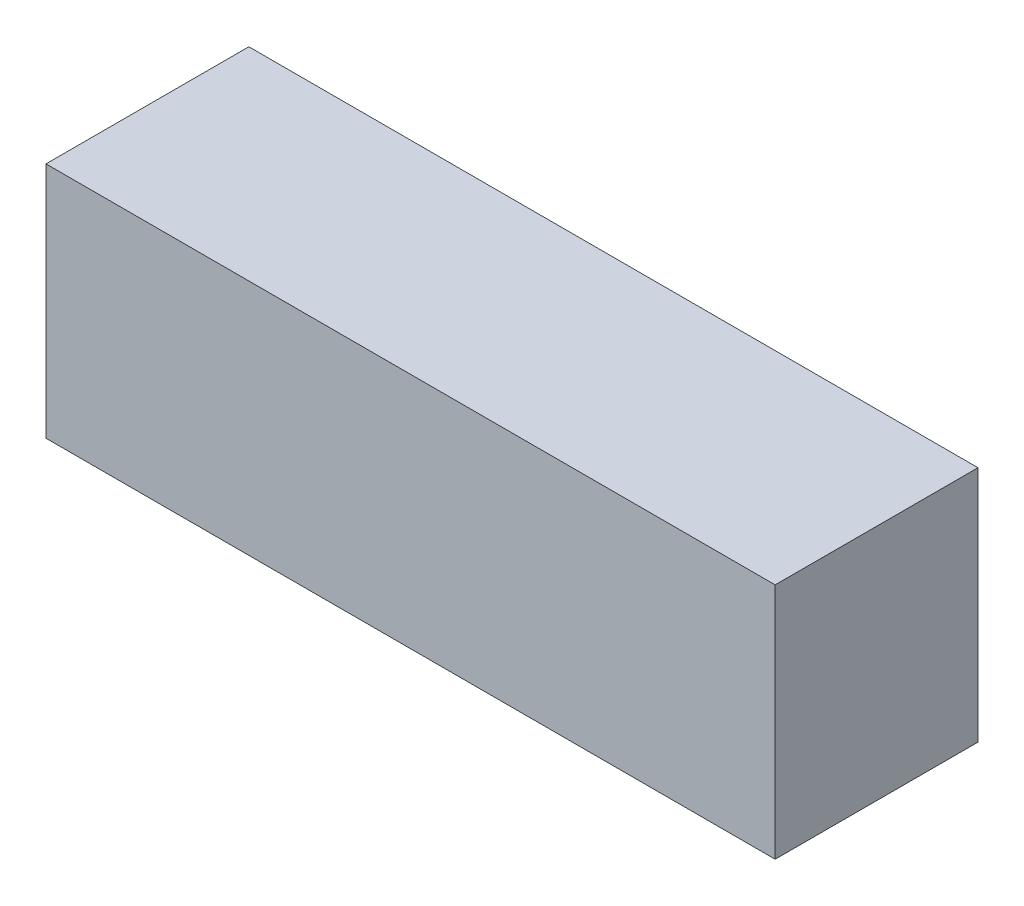
SolidWorks part; units mm, degrees
ref_plane "Front Plane" through (0, 0, 0) normal (0, 0, 1) x (1, 0, 0)
ref_plane "Top Plane" through (0, 0, 0) normal (0, 1, 0) x (1, 0, 0)
ref_plane "Right Plane" through (0, 0, 0) normal (1, 0, 0) x (0, 0, -1)
sketch "Block Profile" plane through (0, 0, 0) normal (0, 1, 0) x (1, 0, 0)
  line L1 (0, 0) -> (71.8566, 0)
  line L2 (0, 0) -> (0, 19.9898)
  line L3 (0, 19.9898) -> (71.8566, 19.9898)
  line L4 (71.8566, 0) -> (71.8566, 19.9898)
  dimension "D1" = 19.9898
  dimension "D2" = 71.8566
extrude "Extrude Profile" add sketch "Block Profile" along normal blind 23.4188
